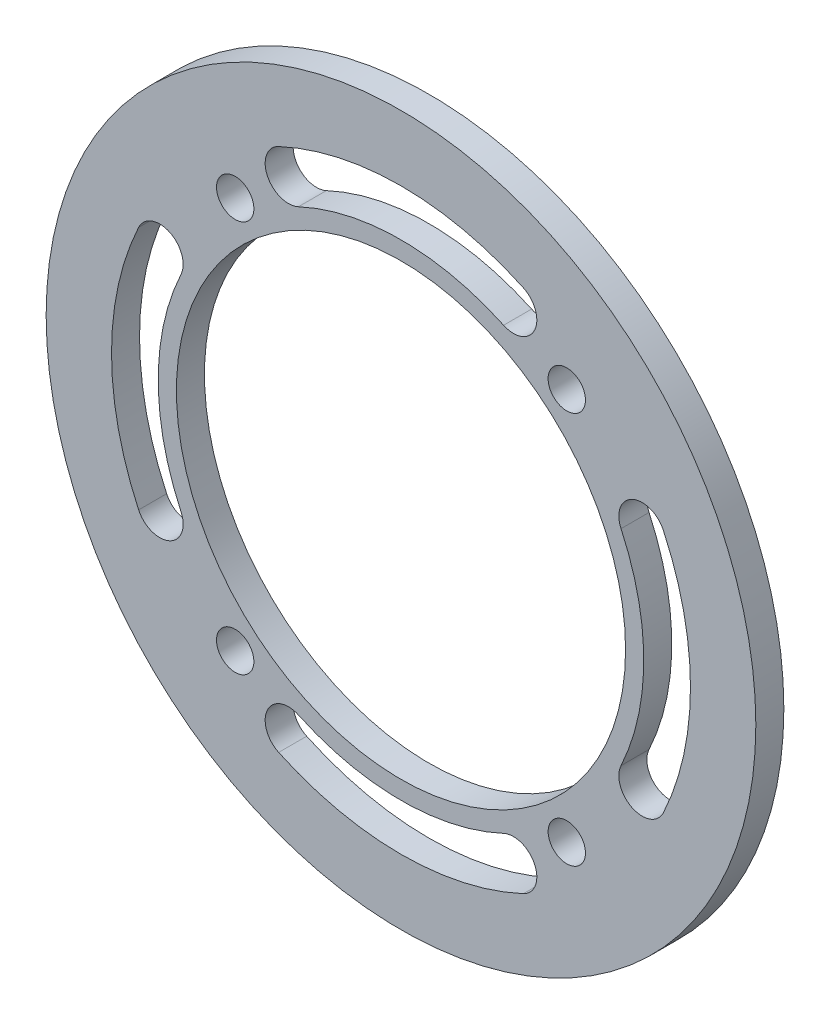
SolidWorks part; units mm, degrees
material "Thornel Mat VMA"
ref_plane "前视基准面" through (0, 0, 0) normal (0, 0, 1) x (1, 0, 0)
ref_plane "上视基准面" through (0, 0, 0) normal (0, 1, 0) x (1, 0, 0)
ref_plane "右视基准面" through (0, 0, 0) normal (1, 0, 0) x (0, 0, -1)
sketch "草图1" plane through (0, 0, 0) normal (0, 0, 1) x (1, 0, 0)
  circle A0 centre (0, 0) radius 35 construction
  circle A1 centre (0, 0) radius 38
  circle A2 centre (0, 0) radius 24.05
  dimension "D1" = 70
  dimension "D4" = 48.1
  dimension "D2" = 3
extrude "凸台-拉伸1" add sketch "草图1" along normal blind 3
sketch "草图3" plane through (0, 0, 3) normal (0, 0, 1) x (1, 0, 0)
  line L0 (17.7553, -21) -> (0, 0) construction
  line L1 (-38, 25) -> (38, 25) construction
  line L2 (-38, 25) -> (-38, -25) construction
  line L3 (-38, -25) -> (38, -25) construction
  line L4 (38, 25) -> (38, -25) construction
  line L5 (-38, 25) -> (38, -25) construction
  line L6 (-38, -25) -> (38, 25) construction
  line L7 (0, 0) -> (20.0288, 0) construction
  line L8 (0, 0) -> (0, 12.8382) construction
  circle A0 centre (0, 0) radius 38 construction
  circle A1 centre (17.7553, -21) radius 2
  circle A2 centre (17.7553, 21) radius 2
  circle A3 centre (-17.7553, -21) radius 2
  circle A4 centre (-17.7553, 21) radius 2
  point P0 (0, 0)
  dimension "D3" = 4
  dimension "D1" = 50
  dimension "D2" = 27.5
  dimension "D4" = 4
extrude "切除-拉伸1" cut sketch "草图3" against normal blind 10
sketch "草图4" plane through (0, 0, 3) normal (0, 0, 1) x (1, 0, 0)
  line L0 (28.5, 0) -> (0, 0) construction
  line L1 (0, 0) -> (25.8298, 12.0446) construction
  arc A0 (25.8298, 12.0446) -> (25.8298, -12.0446) centre (0, 0) cw construction
  arc A1 (28.0955, -13.1012) -> (28.0955, 13.1012) centre (0, 0) ccw
  arc A2 (23.564, -10.9881) -> (23.564, 10.9881) centre (0, 0) ccw
  arc A3 (23.564, -10.9881) -> (28.0955, -13.1012) centre (25.8298, -12.0446) ccw
  arc A4 (28.0955, 13.1012) -> (23.564, 10.9881) centre (25.8298, 12.0446) ccw
  arc A5 (12.0446, -25.8298) -> (-12.0446, -25.8298) centre (0, 0) cw construction
  arc A6 (-13.1012, -28.0955) -> (13.1012, -28.0955) centre (0, 0) ccw
  arc A7 (-10.9881, -23.564) -> (10.9881, -23.564) centre (0, 0) ccw
  arc A8 (-10.9881, -23.564) -> (-13.1012, -28.0955) centre (-12.0446, -25.8298) ccw
  arc A9 (13.1012, -28.0955) -> (10.9881, -23.564) centre (12.0446, -25.8298) ccw
  arc A10 (-25.8298, -12.0446) -> (-25.8298, 12.0446) centre (0, 0) cw construction
  arc A11 (-28.0955, 13.1012) -> (-28.0955, -13.1012) centre (0, 0) ccw
  arc A12 (-23.564, 10.9881) -> (-23.564, -10.9881) centre (0, 0) ccw
  arc A13 (-23.564, 10.9881) -> (-28.0955, 13.1012) centre (-25.8298, 12.0446) ccw
  arc A14 (-28.0955, -13.1012) -> (-23.564, -10.9881) centre (-25.8298, -12.0446) ccw
  arc A15 (-12.0446, 25.8298) -> (12.0446, 25.8298) centre (0, 0) cw construction
  arc A16 (13.1012, 28.0955) -> (-13.1012, 28.0955) centre (0, 0) ccw
  arc A17 (10.9881, 23.564) -> (-10.9881, 23.564) centre (0, 0) ccw
  arc A18 (10.9881, 23.564) -> (13.1012, 28.0955) centre (12.0446, 25.8298) ccw
  arc A19 (-13.1012, 28.0955) -> (-10.9881, 23.564) centre (-12.0446, 25.8298) ccw
  point P4 (28.5, 0)
  point P17 (0, -28.5)
  point P24 (-28.5, 0)
  point P31 (0, 28.5)
  point P36 (0, 0)
  dimension "D2" = 26
  dimension "D3" = 2.5
  dimension "D1" = 25
  dimension "D4" = 4
extrude "切除-拉伸2" cut sketch "草图4" against normal blind 10
